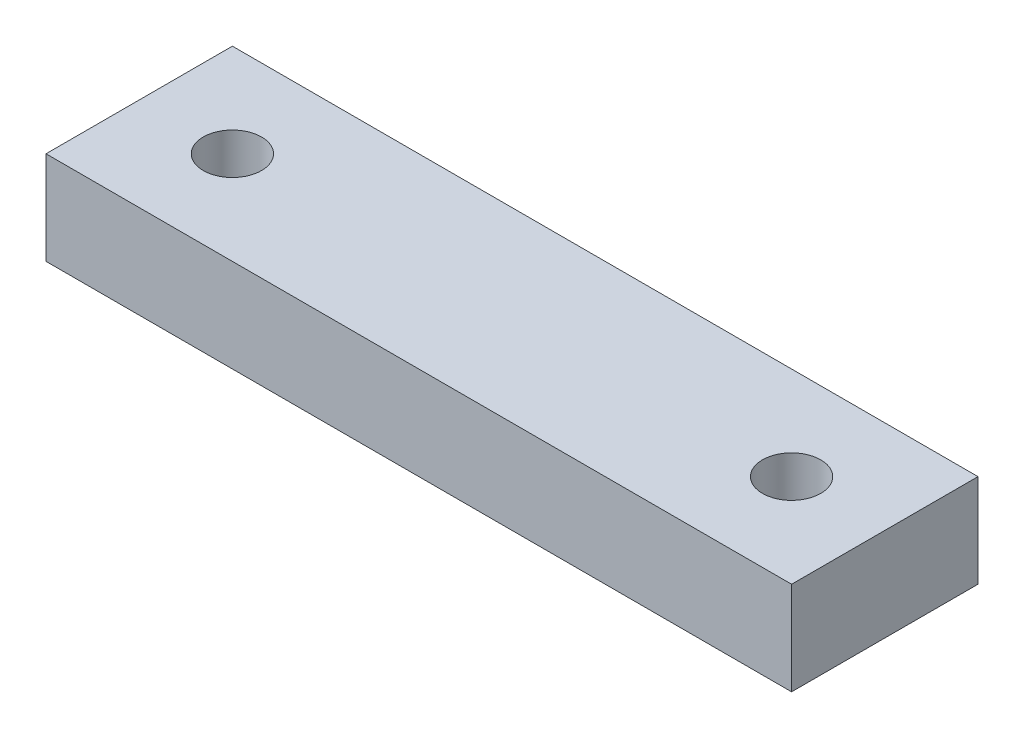
SolidWorks part; units mm, degrees
material "PBT Общее назначение"
ref_plane "Спереди" through (0, 0, 0) normal (0, 0, 1) x (1, 0, 0)
ref_plane "Сверху" through (0, 0, 0) normal (0, 1, 0) x (1, 0, 0)
ref_plane "Справа" through (0, 0, 0) normal (1, 0, 0) x (0, 0, -1)
sketch "Эскиз1" plane through (0, 0, 0) normal (0, 1, 0) x (1, 0, 0)
  line L0 (0, 0) -> (32, 0)
  line L1 (0, 0) -> (0, 8)
  line L2 (32, 0) -> (32, 8)
  line L3 (0, 8) -> (32, 8)
  line L4 (0, 4) -> (32, 4) construction
  line L5 (16, 8) -> (16, 0) construction
  circle A0 centre (4, 4) radius 1.25
  circle A1 centre (28, 4) radius 1.25
  dimension "D3" = 12
  dimension "D4" = 2.5
  dimension "D1" = 8
  dimension "D2" = 32
extrude "Бобышка-Вытянуть1" add sketch "Эскиз1" along normal blind 4
